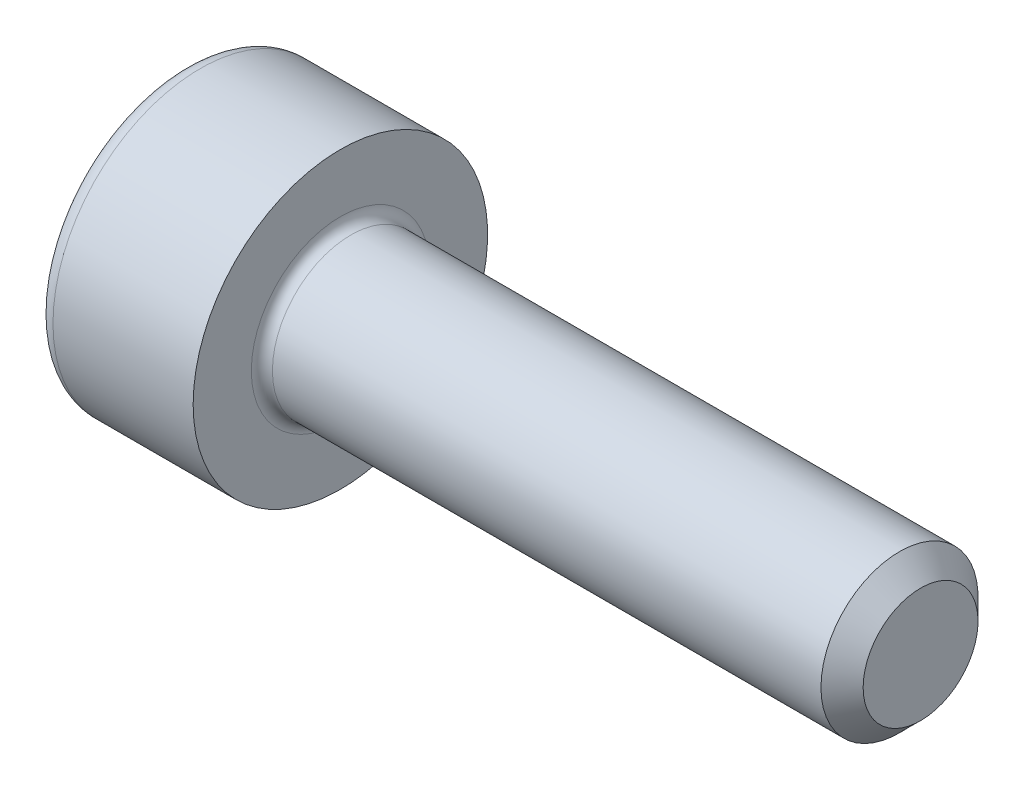
SolidWorks part; units mm, degrees
ref_plane "Спереди" through (0, 0, 0) normal (0, 0, 1) x (1, 0, 0)
ref_plane "Сверху" through (0, 0, 0) normal (0, 1, 0) x (1, 0, 0)
ref_plane "Справа" through (0, 0, 0) normal (1, 0, 0) x (0, 0, -1)
sketch "Sketch1" plane through (0, 0, 0) normal (0, 0, 1) x (1, 0, 0)
  line L0 (0, 0) -> (1.4887, 0)
  line L1 (1.4887, 0) -> (1.4887, 1.3957)
  line L2 (1.4887, 1.3957) -> (0, 1.3957)
  line L3 (0, 1.3957) -> (0, 0)
  line L4 (1.4887, 0) -> (6.9887, 0)
  line L5 (6.9887, 0) -> (6.9887, 0.7444)
  line L6 (6.9887, 0.7444) -> (1.4887, 0.7444)
  dimension "D1" = 5.5
revolve "Revolve1" add sketch "Sketch1" angle 360 about L0
fillet "Fillet1" radius 0.1 1 edges at (1.4887, 0, 0.7444)
fillet "Fillet2" radius 0.16 1 edges at (0, 0, 1.3957)
chamfer "Chamfer1" distance 0.2 angle 45 1 edges at (6.9887, 0, 0.7444)
sketch "Sketch2" plane through (0, 0, 0) normal (-1, 0, 0) x (0, 0, 1)
  line L1 (0, 0.8776) -> (-0.76, 0.4388)
  line L2 (-0.76, 0.4388) -> (-0.76, -0.4388)
  line L3 (-0.76, -0.4388) -> (0, -0.8776)
  line L4 (0, -0.8776) -> (0.76, -0.4388)
  line L5 (0.76, -0.4388) -> (0.76, 0.4388)
  line L6 (0.76, 0.4388) -> (0, 0.8776)
  circle A0 centre (0, 0) radius 0.76 construction
extrude "Extrude1" cut sketch "Sketch2" against normal blind 0.7
